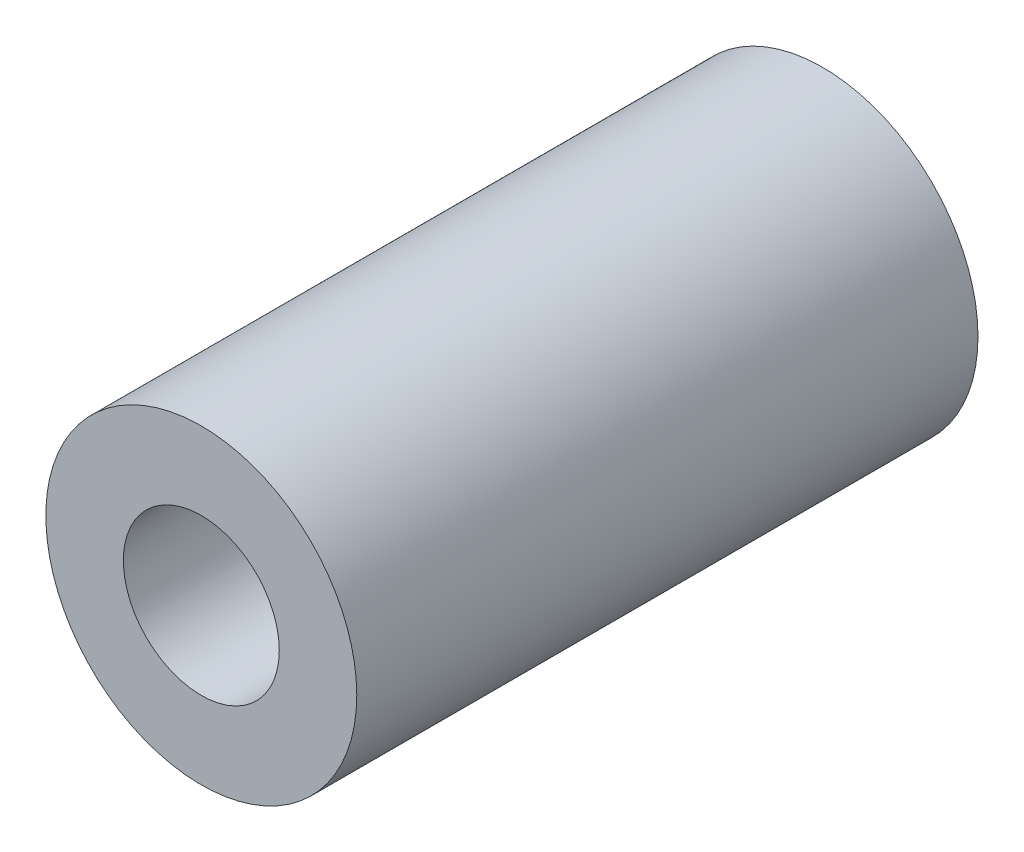
SolidWorks part; units mm, degrees
ref_plane "Front Plane" through (0, 0, 0) normal (0, 0, 1) x (1, 0, 0)
ref_plane "Top Plane" through (0, 0, 0) normal (0, 1, 0) x (1, 0, 0)
ref_plane "Right Plane" through (0, 0, 0) normal (1, 0, 0) x (0, 0, -1)
sketch "Sketch1" plane through (0, 0, 0) normal (0, 0, 1) x (1, 0, 0)
  circle A0 centre (0, 0) radius 6.3563
  circle A1 centre (0, 0) radius 3.1877
  dimension "D1" = 12.7127
  dimension "ID" = 6.3754
extrude "Extrude1" add sketch "Sketch1" along normal mid plane 25.4
sketch "Sketch2" plane through (0, 0, 0) normal (1, 0, 0) x (0, 0, -1)
  line L0 (-12.7, -3.1877) -> (12.7, -3.1877) construction
  line L3 (12.7, 3.1877) -> (-12.7, 3.1877) construction
  line L5 (-12.7, -3.1877) -> (12.7, -3.1877)
  line L6 (12.7, 3.1877) -> (-12.7, 3.1877)
sketch "Sketch4" plane through (0, 0, 12.7) normal (0, 0, 1) x (1, 0, 0)
  line L0 (0, 0) -> (-2.254, 2.254)
  line L1 (0, -7.8791) -> (0, 7.8791) construction
  circle A0 centre (0, 0) radius 3.1877 construction
  dimension "D1" = 45
